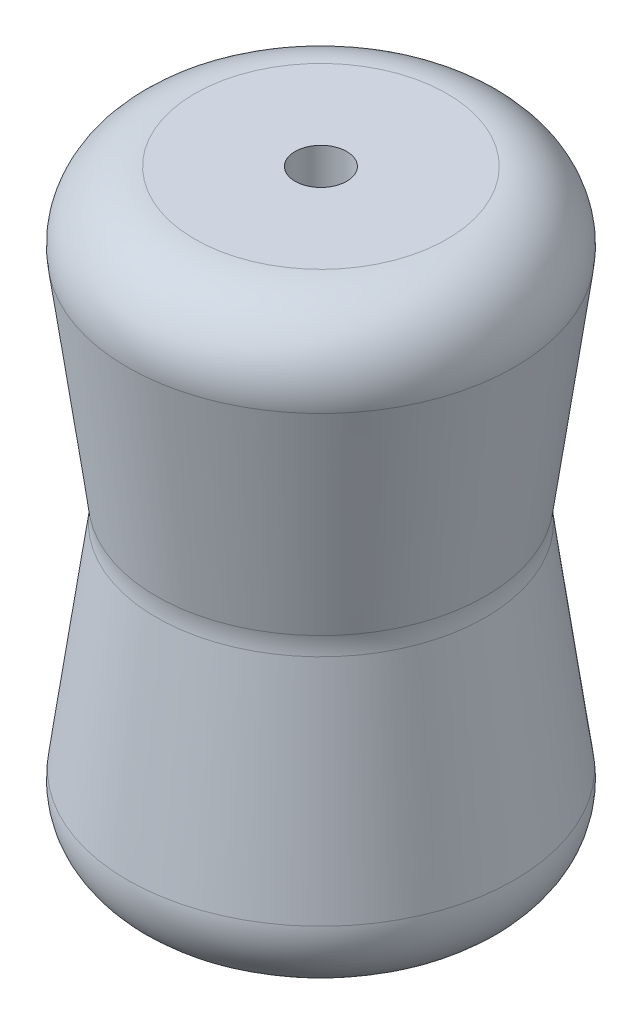
SolidWorks part; units mm, degrees
ref_plane "前视基准面" through (0, 0, 0) normal (0, 0, 1) x (1, 0, 0)
ref_plane "上视基准面" through (0, 0, 0) normal (0, 1, 0) x (1, 0, 0)
ref_plane "右视基准面" through (0, 0, 0) normal (1, 0, 0) x (0, 0, -1)
other "Configuration Table"
sketch "草图2" plane through (0, 0, 0) normal (0, 0, 1) x (1, 0, 0)
  line L0 (0, 0) -> (0, 44)
  line L1 (0, 22) -> (-12, 22) construction
  line L2 (-12, 22) -> (-15, 0)
  line L3 (-15, 0) -> (0, 0)
  line L4 (-12, 22) -> (-15, 44)
  line L5 (-15, 44) -> (0, 44)
  dimension "D1" = 15
  dimension "D2" = 12
  dimension "D3" = 22
revolve "旋转1" add sketch "草图2" angle 360 about L0
sketch "草图3" plane through (0, 0, 0) normal (0, -1, 0) x (1, 0, 0)
  circle A0 centre (0, 0) radius 1.9
  dimension "D1" = 3.8
extrude "切除-拉伸1" cut sketch "草图3" against normal blind 60
fillet "圆角1" radius 5 3 edges at (15, 0, 0) (12, 22, 0) (15, 44, 0)
